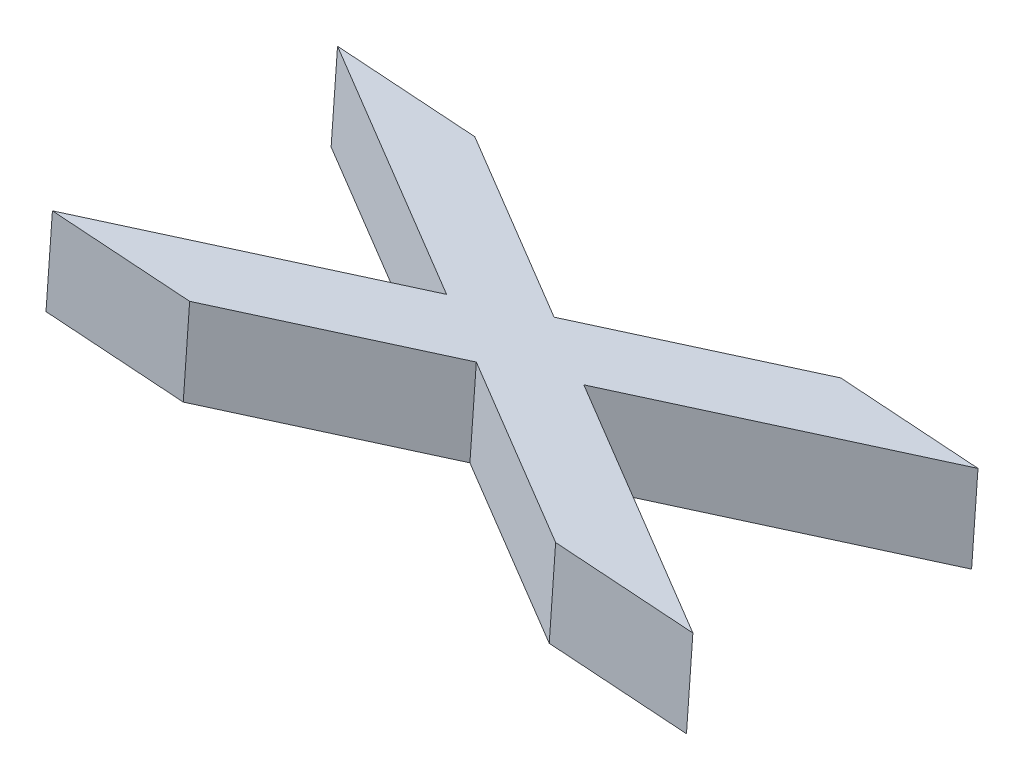
SolidWorks part; units mm, degrees
material "ABS"
ref_plane "Front Plane" through (0, 0, 0) normal (0, 0, 1) x (1, 0, 0)
ref_plane "Top Plane" through (0, 0, 0) normal (0, 1, 0) x (1, 0, 0)
ref_plane "Right Plane" through (0, 0, 0) normal (1, 0, 0) x (0, 0, -1)
sketch "Sketch1" plane through (3.3321, 47.0487, 0) normal (0.0706, 0.9975, 0) x (0.9975, -0.0706, 0)
  line L0 (-69.6588, -66.6891) -> (-51.6815, -56.5291)
  line L2 (-33.7042, -38.7491) -> (-51.6815, -48.9091)
  line L3 (-58.423, -52.7191) -> (-83.1418, -38.7491)
  line L4 (-58.423, -52.7191) -> (-83.1418, -66.6891)
  line L5 (-69.6588, -38.7491) -> (-51.6815, -48.9091)
  line L7 (-33.7042, -66.6891) -> (-51.6815, -56.5291)
  line L8 (-83.1418, -38.7491) -> (-69.6588, -38.7491)
  line L9 (-20.2212, -38.7491) -> (-83.1418, -38.7491) construction
  line L10 (-83.1418, -66.6891) -> (-69.6588, -66.6891)
  line L11 (-20.2212, -66.6891) -> (-83.1418, -66.6891) construction
  line L12 (-20.2212, -66.6891) -> (-33.7042, -66.6891)
  line L13 (-20.2212, -38.7491) -> (-33.7042, -38.7491)
  line L14 (-44.94, -52.7191) -> (-20.2212, -66.6891)
  line L15 (-44.94, -52.7191) -> (-20.2212, -38.7491)
extrude "Boss-Extrude1" add sketch "Sketch1" against normal blind 8.89
